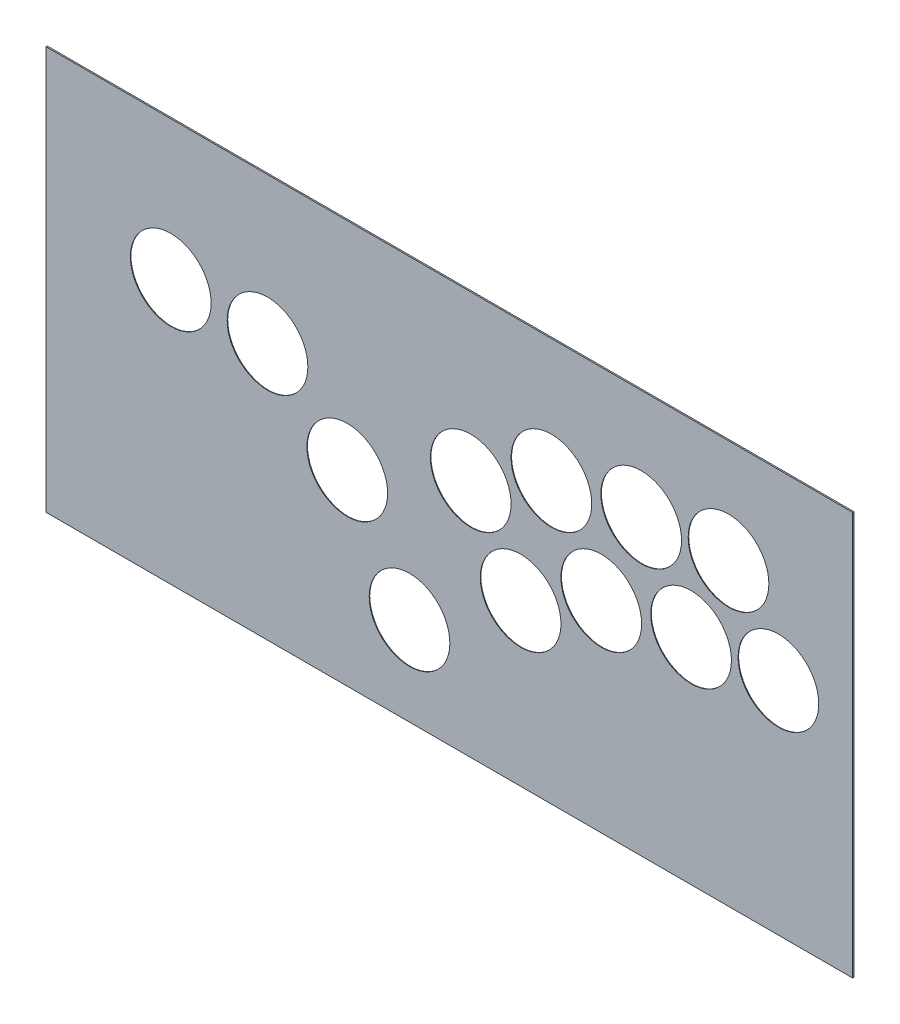
SolidWorks part; units mm, degrees
ref_plane "Front Plane" through (0, 0, 0) normal (0, 0, 1) x (1, 0, 0)
ref_plane "Top Plane" through (0, 0, 0) normal (0, 1, 0) x (1, 0, 0)
ref_plane "Right Plane" through (0, 0, 0) normal (1, 0, 0) x (0, 0, -1)
sketch "Sketch1" plane through (0, 0, 0) normal (0, 0, 1) x (1, 0, 0)
  line L0 (-2223.8502, 1518.0211) -> (2856.1498, 1518.0211)
  line L1 (2856.1498, 1518.0211) -> (2856.1498, -1021.9789)
  line L2 (2856.1498, -1021.9789) -> (-2223.8502, -1021.9789)
  line L3 (-2223.8502, -1021.9789) -> (-2223.8502, 1518.0211)
  circle A0 centre (-1438.6973, 638.6197) radius 254
  circle A1 centre (-829.2347, 595.7784) radius 254
  circle A2 centre (-326.9042, 157.8449) radius 254
  circle A3 centre (65.1772, -464.0222) radius 254
  circle A4 centre (450.8528, 488.0072) radius 254
  circle A5 centre (958.8528, 742.0072) radius 254
  circle A6 centre (1524.5544, 825.9777) radius 254
  circle A7 centre (2074.4992, 864.0589) radius 254
  circle A8 centre (765.1069, -9.4281) radius 254
  circle A9 centre (1273.1069, 244.5719) radius 254
  circle A10 centre (1838.8085, 328.5423) radius 254
  circle A11 centre (2388.7533, 366.6235) radius 254
extrude "Boss-Extrude1" add sketch "Sketch1" along normal blind 8
chamfer "Chamfer1" distance 5 angle 45 2 edges at (2328.4992, 864.0589, 0) (2642.7533, 366.6235, 0)
chamfer "Chamfer2" distance 5 angle 45 10 edges at (-575.2347, 595.7784, 0) (-1184.6973, 638.6197, 0) (-72.9042, 157.8449, 0) (319.1772, -464.0222, 0) (704.8528, 488.0072, 0) (1019.1069, -9.4281, 0) (1212.8528, 742.0072, 0) (1527.1069, 244.5719, 0) (2092.8085, 328.5423, 0) (1778.5544, 825.9777, 0)
